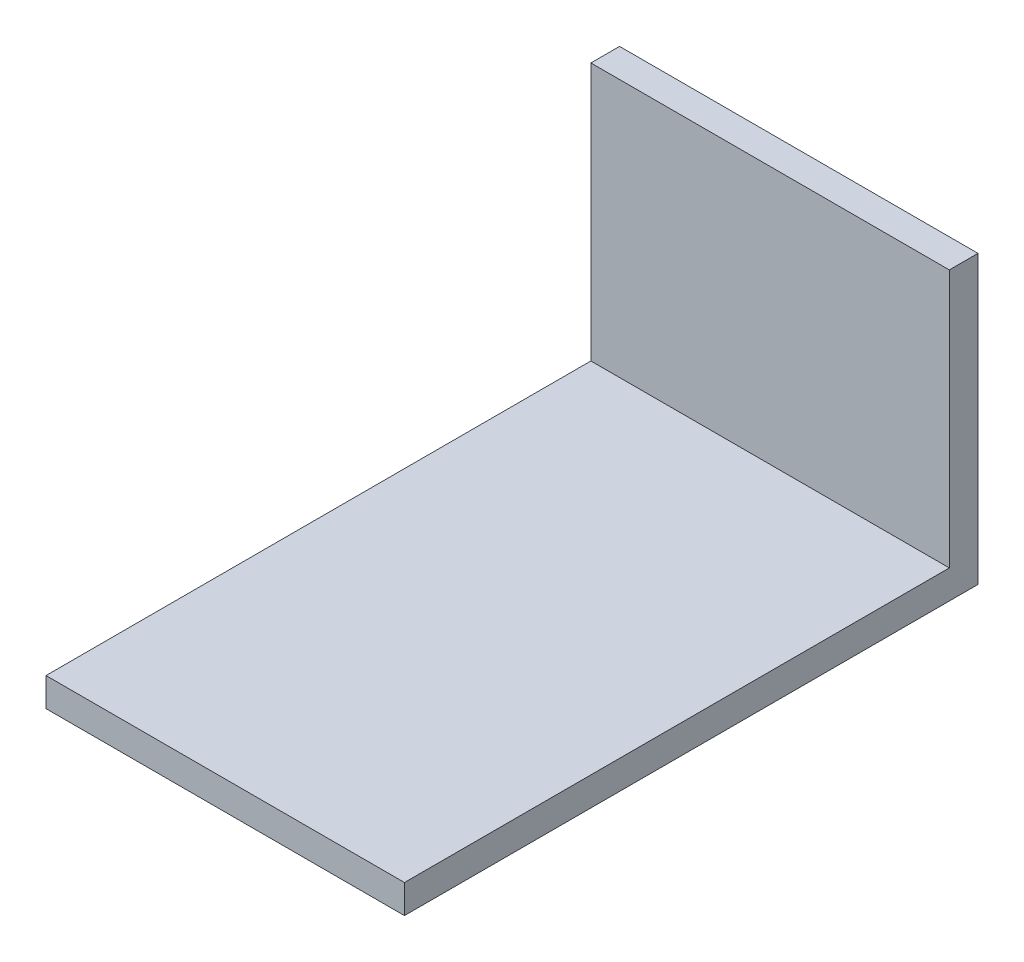
SolidWorks part; units mm, degrees
ref_plane "Спереди" through (0, 0, 0) normal (0, 0, 1) x (1, 0, 0)
ref_plane "Сверху" through (0, 0, 0) normal (0, 1, 0) x (1, 0, 0)
ref_plane "Справа" through (0, 0, 0) normal (1, 0, 0) x (0, 0, -1)
sketch "Эскиз1" plane through (0, 0, 0) normal (1, 0, 0) x (0, 0, -1)
  line L0 (0, 0) -> (0, 40)
  line L1 (0, 40) -> (-4, 40)
  line L2 (-4, 40) -> (-4, 4)
  line L3 (-4, 4) -> (-80, 4)
  line L4 (-80, 4) -> (-80, 0)
  line L5 (-80, 0) -> (0, 0)
  point P3 (-80, 2)
  dimension "D1" = 4
  dimension "D2" = 4
  dimension "D3" = 80
  dimension "D4" = 40
extrude "Бобышка-Вытянуть1" add sketch "Эскиз1" along normal blind 50
